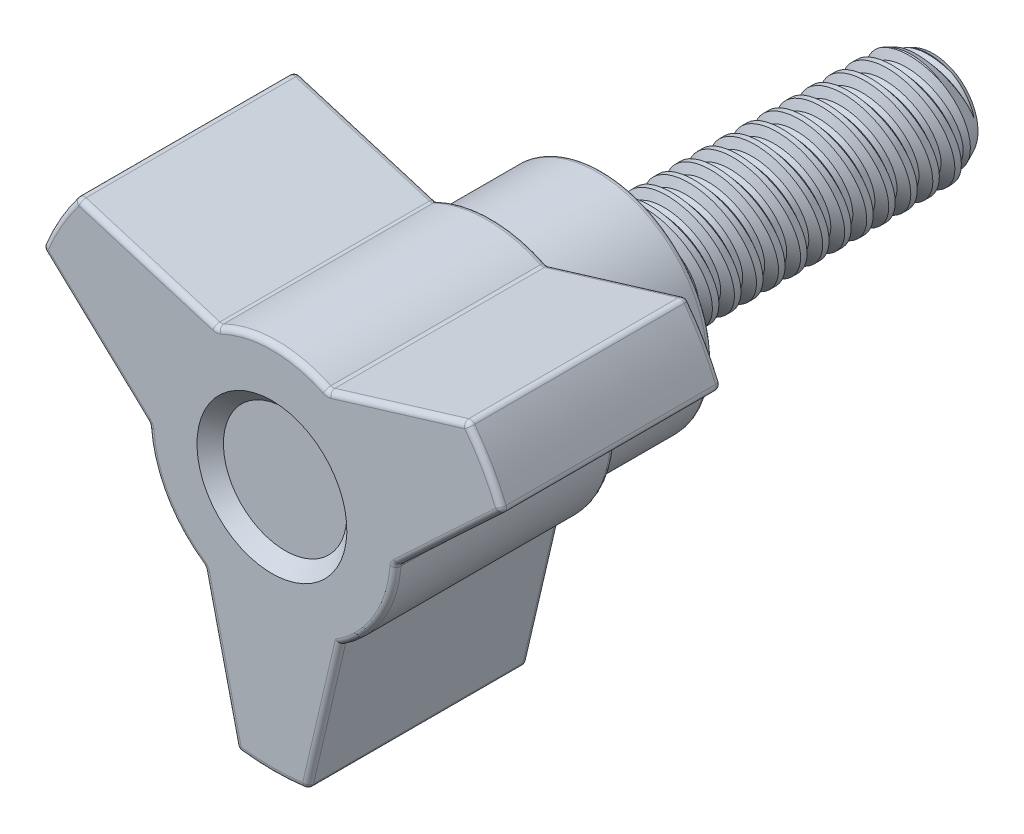
SolidWorks part; units mm, degrees
ref_plane "Front" through (0, 0, 0) normal (0, 0, 1) x (1, 0, 0)
ref_plane "Top" through (0, 0, 0) normal (0, 1, 0) x (1, 0, 0)
ref_plane "Right" through (0, 0, 0) normal (1, 0, 0) x (0, 0, -1)
sketch "Sketch1" plane through (0, 0, 0) normal (1, 0, 0) x (0, 0, -1)
  line L0 (9.525, 0) -> (-9.525, 0)
  line L1 (-9.525, 3.175) -> (-9.525, 4.5339) construction
  line L4 (-9.525, 3.175) -> (9.525, 3.175)
  line L5 (9.525, 3.175) -> (9.525, 0)
  line L6 (-9.525, 0) -> (-9.525, 3.175)
  line L7 (-8.5598, 0) -> (-9.525, 0) construction
  line L10 (-9.525, -3.175) -> (9.525, -3.175) construction
  dimension "Screw Dia" = 6.35
  dimension "Thread Length" = 19.05
revolve "Revolve1" add sketch "Sketch1" angle 360 about L7
sketch "Sketch2" plane through (0, 0, 0) normal (1, 0, 0) x (0, 0, -1)
  line L0 (-9.525, 3.175) -> (-9.525, -3.175) construction
  line L1 (-9.525, -3.175) -> (-8.255, -3.175) construction
  line L2 (-8.255, -3.175) -> (-9.525, 3.175) construction
  line L3 (-9.525, 3.175) -> (-9.3693, 3.2061) construction
  line L4 (-9.3693, 3.2061) -> (-8.2797, 3.4241)
  line L5 (-8.2797, 3.4241) -> (-8.534, 2.6722)
  line L6 (-8.534, 2.6722) -> (-8.8454, 2.6099)
  line L7 (-8.8454, 2.6099) -> (-9.3693, 3.2061)
  line L8 (-8.6897, 2.641) -> (-8.8245, 3.3151) construction
  line L9 (-9.525, 3.175) -> (-8.7965, 3.175) construction
  line L10 (-8.7965, 3.175) -> (-7.5265, -3.175) construction
  line L11 (-7.5265, -3.175) -> (-8.255, -3.175) construction
  line L12 (-9.525, -3.175) -> (9.525, -3.175) construction
  line L13 (-9.525, 3.175) -> (9.525, 3.175) construction
  line L14 (-9.525, 0) -> (-9.525, 3.175) construction
  line L15 (-9.525, -0.2727) -> (-6.798, 0.2727) construction
  point P19 (-8.1615, 0)
  dimension "D1" = 0.1588
  dimension "D2" = 0.3175
  dimension "Thread Pitch" = 1.27
  dimension "D4" = 1.27
  dimension "D3" = 60
revolve "Cut-Revolve1" cut sketch "Sketch2" angle 360 about L15
pattern_linear "LPattern1" count 15 spacing 1.27 along (0, 0, -1) count 2 spacing 1.27 along (0, 0, 1) of "Cut-Revolve1"
sketch "Sketch5" plane through (0, 0, 0) normal (1, 0, 0) x (0, 0, -1)
  line L0 (-9.525, 0) -> (9.525, 0) construction
  line L2 (-9.525, 6.35) -> (-15.875, 6.35)
  line L3 (-15.875, 6.35) -> (-15.875, 14.2875)
  line L4 (-9.525, 0) -> (-9.525, -6.35) construction
  line L5 (-9.525, 0) -> (-9.525, 3.175) construction
  line L7 (-28.575, 0) -> (-9.525, 0) construction
  line L8 (-9.525, 3.175) -> (-9.525, -3.175) construction
  line L10 (-9.525, 6.35) -> (-9.525, 0)
  line L12 (-28.575, 14.2875) -> (-15.875, 14.2875)
  line L13 (-28.575, 14.2875) -> (-28.575, 0)
  line L14 (-15.875, -6.35) -> (-15.875, -14.2875) construction
  line L18 (-9.525, 0) -> (-28.575, 0)
  dimension "D" = 6.35
  dimension "A" = 28.575
  dimension "C" = 12.7
  dimension "B" = 12.7
  dimension "D1" = 14.2875
revolve "Revolve3" add sketch "Sketch5" angle 360 about L0
sketch "Sketch6" plane through (0, 0, 28.575) normal (0, 0, 1) x (1, 0, 0)
  line L0 (0, 0) -> (0, 17.4625) construction
  line L1 (0, 0) -> (15.123, -8.7313) construction
  line L2 (0, 0) -> (12.3733, 7.1437) construction
  line L3 (11.2316, 8.8309) -> (3.1939, 6.39)
  line L4 (0, 17.4625) -> (0, 7.1437)
  line L5 (6.1867, -3.5719) -> (15.123, -8.7313)
  line L6 (13.2636, 5.3114) -> (7.1309, -0.4291)
  arc A0 (3.1939, 6.39) -> (0, 7.1437) centre (0, 0) ccw
  arc A2 (13.2636, 5.3114) -> (11.2316, 8.8309) centre (0, 0) ccw
  arc A3 (7.1309, -0.4291) -> (6.1867, -3.5719) centre (0, 0) cw
  arc A4 (15.123, -8.7313) -> (0, 17.4625) centre (0, 0) ccw
  circle A5 centre (0, 0) radius 7.1438 construction
  circle A6 centre (0, 0) radius 14.2875 construction
  dimension "D3" = 60
  dimension "D2" = 14.2875
  dimension "D6" = 17.4625
  dimension "D1" = 120
  dimension "D4" = 4.064
  dimension "D5" = 7.874
extrude "Cut-Extrude1" cut sketch "Sketch6" against normal up to next
pattern_circular "CirPattern1" count 3 over 360 about axis through (0, 0, 0) along (0, 0, 1) of "Cut-Extrude1"
sketch "Sketch10" plane through (0, 0, 0) normal (1, 0, 0) x (0, 0, -1)
  line L0 (-28.575, 4.318) -> (-28.575, -4.318) construction
  line L1 (-28.575, 14.2875) -> (-28.575, 0) construction
  line L2 (-28.575, 7.1438) -> (-28.575, -7.1437) construction
  line L3 (-9.525, 0) -> (-28.575, 0) construction
  line L4 (-28.575, 0) -> (-28.575, 4.318)
  line L5 (-28.575, 4.318) -> (-27.813, 3.556)
  line L6 (-27.813, 3.556) -> (-27.813, 0)
  line L7 (-27.813, 0) -> (-28.575, 0)
  line L8 (9.525, 0) -> (-28.575, 0) construction
  point P6 (-28.575, 0)
  dimension "D1" = 45
  dimension "D2" = 8.636
  dimension "D3" = 0.762
revolve "Cut-Revolve3" cut sketch "Sketch10" angle 360 about L8
fillet "Fillet4" radius 0.3175 36 edges at (0, -6.35, 9.525) (6.1867, -3.5719, 15.875) (6.1867, -3.5719, 28.575) (7.2127, 7.6105, 15.875) (-11.2316, 8.8309, 22.225) (-12.3733, 7.1437, 28.575) (-13.2636, 5.3114, 22.225) (-12.3733, 7.1437, 15.875) (-2.032, -14.1423, 22.225) (0, -14.2875, 15.875) (-2.9845, -10.0516, 15.875) (-3.937, -5.961, 22.225) (-7.1309, -0.4291, 22.225) (-6.1867, -3.5719, 15.875) (-10.1972, 2.4412, 15.875) (-10.1972, 2.4412, 28.575) (-6.1867, -3.5719, 28.575) (-2.9845, -10.0516, 28.575) (0, -14.2875, 28.575) (2.9845, -10.0516, 28.575) (2.032, -14.1423, 22.225) (2.9845, -10.0516, 15.875) (10.1972, 2.4412, 15.875) (7.1309, -0.4291, 22.225) (10.1972, 2.4412, 28.575) (13.2636, 5.3114, 22.225) (12.3733, 7.1437, 15.875) (12.3733, 7.1437, 28.575) (11.2316, 8.8309, 22.225) (7.2127, 7.6105, 28.575) (3.1939, 6.39, 22.225) (-3.1939, 6.39, 22.225) (0, 7.1438, 28.575) (-7.2127, 7.6105, 28.575) (-7.2127, 7.6105, 15.875) (0, 7.1438, 15.875)
sketch "Sketch11" plane through (0, 0, 0) normal (1, 0, 0) x (0, 0, -1)
  line L0 (8.255, 3.175) -> (9.525, 2.5828)
  line L1 (-9.525, 3.175) -> (9.525, 3.175) construction
  line L2 (9.525, 3.175) -> (9.525, 0) construction
  line L3 (9.525, 2.5828) -> (9.525, 3.175)
  line L4 (9.525, 3.175) -> (8.255, 3.175)
  line L5 (0, 0) -> (9.525, 0) construction
  dimension "D1" = 25
  dimension "D2" = 1.27
revolve "Cut-Revolve4" cut sketch "Sketch11" angle 360 about L5
sketch "Sketch12" plane through (0, 0, 9.525) normal (0, 0, -1) x (-1, 0, 0)
  circle A0 centre (0, 0) radius 6.35 construction
  circle A1 centre (0, 0) radius 6.35
equation "\"D1@Sketch2\"=\"Thread Pitch@Sketch2\"/8"
equation "\"D2@Sketch2\"=\"Thread Pitch@Sketch2\"/4"
equation "\"D4@Sketch2\"=\"Thread Pitch@Sketch2\""
equation "\"D3@LPattern1\"=\"Thread Pitch@Sketch2\""
equation "\"D4@LPattern1\"=\"Thread Pitch@Sketch2\""
equation "\"D1@LPattern1\"=\"Thread Length@Sketch1\"/\"Thread Pitch@Sketch2\""
equation "\"D2@Sketch6\" = \"B@Sketch5\"*1.125"
equation "\"D1@Sketch5\" = \"A@Sketch5\"/2"
equation "\"D2@Sketch11\" = \"Thread Pitch@Sketch2\""
equation "\"D6@Sketch6\" = \"D1@Sketch5\"+.125"
